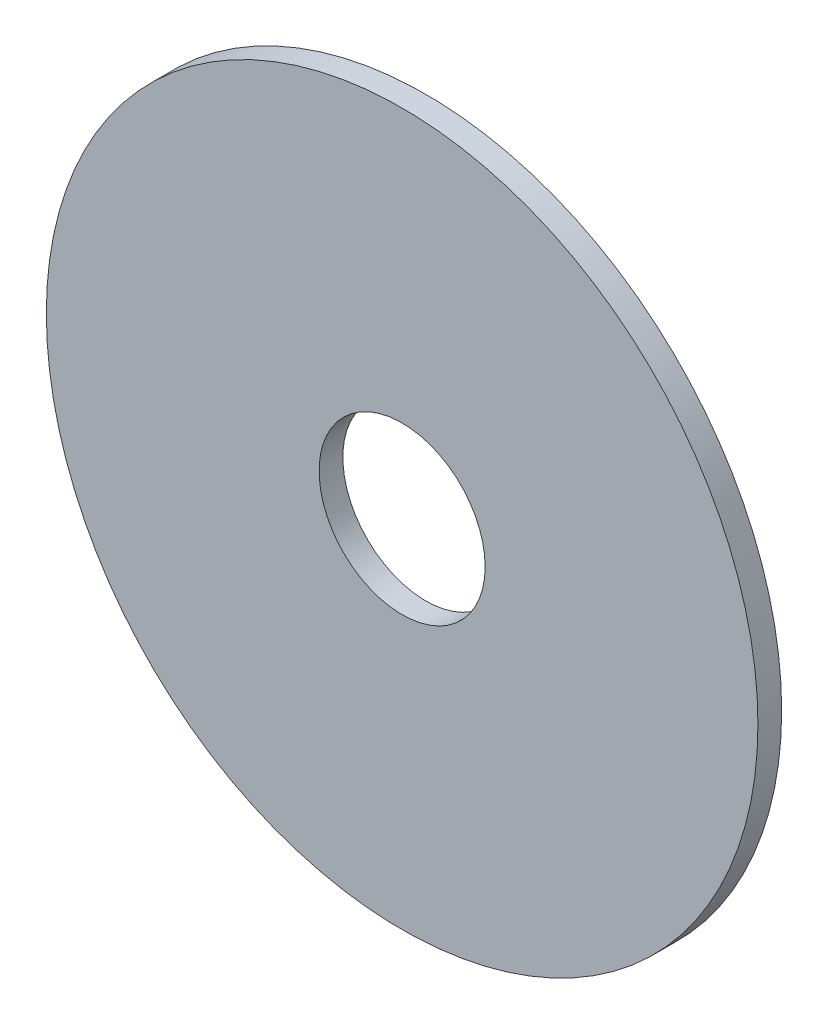
SolidWorks part; units mm, degrees
material "1023 Chapa de acero al carbono (SS)"
ref_plane "Front Plane" through (0, 0, 0) normal (0, 0, 1) x (1, 0, 0)
ref_plane "Top Plane" through (0, 0, 0) normal (0, 1, 0) x (1, 0, 0)
ref_plane "Right Plane" through (0, 0, 0) normal (1, 0, 0) x (0, 0, -1)
sketch "Croquis1" plane through (0, 0, 0) normal (0, 0, 1) x (1, 0, 0)
  circle A0 centre (0, 0) radius 15
  circle A1 centre (0, 0) radius 3.5
  dimension "D1" = 30
  dimension "D2" = 7
extrude "Saliente-Extruir1" add sketch "Croquis1" along normal blind 1
